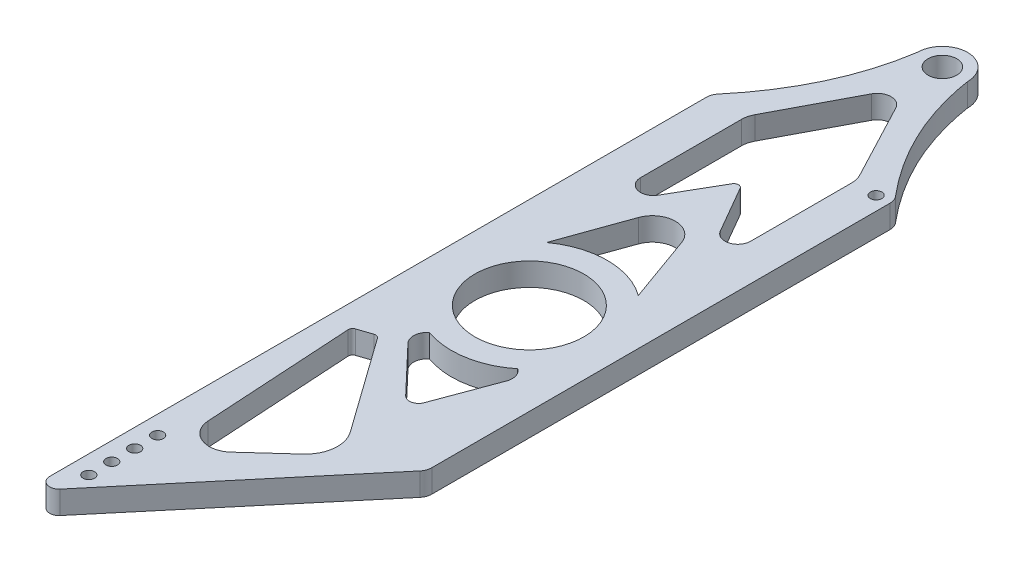
SolidWorks part; units mm, degrees
material "6061-T6 (SS)"
ref_plane "X-Y Datum" through (0, 0, 0) normal (0, 0, 1) x (1, 0, 0)
ref_plane "X-Z Datum" through (0, 0, 0) normal (0, 1, 0) x (1, 0, 0)
ref_plane "Y-Z Datum" through (0, 0, 0) normal (1, 0, 0) x (0, 0, -1)
other "Graphic1" [suppressed]
other "Graphic (Closed) -1" [suppressed]
sketch "Sketch1" plane through (0, 0, 0) normal (0, 1, 0) x (1, 0, 0)
  line L0 (25.4, -39.9268) -> (25.4, -166.6722)
  line L2 (-25.4, -221.6214) -> (-25.4, -39.9268)
  line L6 (25.4, -114.3) -> (-25.4, -114.3) construction
  line L9 (24.5086, -169.1212) -> (-20.9142, -223.2541)
  line L11 (5.6055, -169.4737) -> (-13.1669, -143.1763)
  line L13 (4.3503, -181.2166) -> (-6.1618, -190.7738)
  line L14 (-16.7719, -186.4583) -> (-19.261, -145.2583)
  line L15 (-18.3959, -143.9772) -> (-14.6031, -142.7097)
  line L16 (4.5321, -153.0605) -> (-7.7137, -140.1848)
  line L18 (14.9571, -135.5462) -> (8.7527, -152.1969)
  line L20 (-12.7, -96.8404) -> (-5.9766, -78.1113)
  line L21 (5.9766, -78.1113) -> (12.7, -96.8404)
  line L22 (-3.3709, -16.2433) -> (-14.5081, -37.3849)
  line L23 (-15.24, -40.3445) -> (-15.24, -68.2845)
  line L24 (-8.6044, -70.0625) -> (-1.0999, -57.0642)
  line L25 (1.0999, -57.0642) -> (8.6044, -70.0625)
  line L26 (15.24, -68.2845) -> (15.24, -40.3445)
  line L27 (14.5081, -37.3849) -> (3.3709, -16.2433)
  line L28 (8.89, -40.3445) -> (-8.89, -40.3445) construction
  line L29 (15.24, -55.1592) -> (-15.24, -55.1592) construction
  circle A0 centre (0, 0) radius 3.9688
  circle A2 centre (0, -114.3) radius 15.0813
  circle A6 centre (-20.32, -215.9) radius 1.5875
  circle A7 centre (-20.32, -209.55) radius 1.5875
  circle A8 centre (-20.32, -203.2) radius 1.5875
  circle A9 centre (-20.32, -196.85) radius 1.5875
  arc A10 (6.985, 0) -> (-6.985, 0) centre (0, 0) ccw
  arc A11 (-16.7719, -186.4583) -> (-6.1618, -190.7738) centre (-10.4335, -186.0754) ccw
  arc A12 (-18.3959, -143.9772) -> (-19.261, -145.2583) centre (-17.9933, -145.1817) ccw
  arc A13 (-14.6031, -142.7097) -> (-13.1669, -143.1763) centre (-14.2005, -143.9142) cw
  arc A14 (4.3503, -181.2166) -> (5.6055, -169.4737) centre (-1.6301, -174.6388) ccw
  arc A16 (13.5694, -131.0929) -> (14.9571, -135.5462) centre (11.3869, -134.2158) cw
  arc A17 (4.5321, -153.0605) -> (8.7527, -152.1969) centre (6.3726, -151.3101) ccw
  arc A21 (-3.3709, -16.2433) -> (3.3709, -16.2433) centre (0, -18.0191) cw
  arc A25 (14.5081, -37.3849) -> (15.24, -40.3445) centre (8.89, -40.3445) cw
  arc A26 (-14.5081, -37.3849) -> (-15.24, -40.3445) centre (-8.89, -40.3445) ccw
  arc A27 (13.5694, -131.0929) -> (-7.3523, -134.5995) centre (0, -114.3) cw
  arc A28 (-7.3523, -134.5995) -> (-7.7137, -140.1848) centre (-4.953, -137.5591) ccw
  arc A29 (-15.24, -68.2845) -> (-8.6044, -70.0625) centre (-11.684, -68.2845) ccw
  arc A30 (8.6044, -70.0625) -> (15.24, -68.2845) centre (11.684, -68.2845) ccw
  arc A31 (-1.0999, -57.0642) -> (1.0999, -57.0642) centre (0, -57.6992) cw
  arc A32 (12.7, -96.8404) -> (-12.7, -96.8404) centre (0, -114.3) ccw
  arc A33 (-5.9766, -78.1113) -> (5.9766, -78.1113) centre (0, -80.2568) cw
  arc A34 (24.5041, -37.4724) -> (25.4, -39.9268) centre (21.59, -39.9268) cw
  arc A35 (-24.5041, -37.4724) -> (-25.4, -39.9268) centre (-21.59, -39.9268) ccw
  arc A36 (25.4, -166.6722) -> (24.5086, -169.1212) centre (21.59, -166.6722) cw
  arc A37 (-25.4, -221.6214) -> (-20.9142, -223.2541) centre (-22.86, -221.6214) ccw
  circle A38 centre (21.59, -39.9268) radius 1.5875
  spline S0 degree 3 poles (24.5041, -37.4724) (15.363, -26.6191) (9.1782, -14.2) (6.985, 0) knots 0.031766 0.031766 0.031766 0.031766 1 1 1 1
  spline S1 degree 3 poles (-24.5041, -37.4724) (-15.3415, -26.5935) (-9.1434, -14.1045) (-6.985, 0) knots 0.031078 0.031078 0.031078 0.031078 1 1 1 1
  point P44 (0, -55.1592)
  point P58 (0, -40.3445)
  point P66 (25.4, -168.0589)
  point P68 (-15.24, -81.5557)
  point P71 (15.24, -81.5557)
  point P75 (15.24, -38.7742)
  point P78 (-15.24, -38.7742)
  point P80 (-25.4, -228.6)
  point P85 (-15.24, -81.5557)
  point P88 (15.24, -81.5557)
  point P92 (0, -55.1592)
  dimension "D1" = 7.9375
  dimension "D4" = 30.1625
  dimension "D8" = 3.175
  dimension "D6" = 6.985
  dimension "D18" = 6.35
  dimension "D19" = 1.27
  dimension "D20" = 1.27
  dimension "D21" = 8.89
  dimension "D28" = 3.81
  dimension "D29" = 2.54
  dimension "D32" = 3.81
  dimension "D33" = 6.35
  dimension "D37" = 21.59
  dimension "D41" = 3.81
  dimension "D46" = 3.556
  dimension "D47" = 1.27
  dimension "D49" = 21.59
  dimension "D31" = 6.35
  dimension "D17" = 3.81
  dimension "D52" = 3.81
  dimension "D55" = 3.81
  dimension "D56" = 2.54
  dimension "D43" = 22.352
  dimension "D44" = 22.352
  dimension "D53" = 3.175
  dimension "D2" = 228.6
  dimension "D3" = 114.3
  dimension "D9" = 5.08
  dimension "D10" = 12.7
  dimension "D11" = 6.35
  dimension "D12" = 6.35
  dimension "D13" = 6.35
  dimension "D5" = 50.8
  dimension "D7" = 140
  dimension "D14" = 19.05
  dimension "D16" = 12.7
  dimension "D22" = 18.0165
  dimension "D23" = 6.5799
  dimension "D24" = 107.042
  dimension "D25" = 105.022
  dimension "D26" = 3.999
  dimension "D34" = 32.3103
  dimension "D35" = 41.2751
  dimension "D36" = 27.8194
  dimension "D38" = 21.2136
  dimension "D39" = 16.7929
  dimension "D27" = 64
  dimension "D40" = 4.6645
  dimension "D42" = 5.597
  dimension "D45" = 60
  dimension "D48" = 27.94
  dimension "D30" = 25.4
  dimension "D50" = 30.48
  dimension "D51" = 19.8993
  dimension "D57" = 24.5041
  dimension "D58" = 37.4724
  dimension "D59" = 40.3445
  dimension "D60" = 18.0191
  dimension "D15" = 25.4
extrude "Boss-Extrude1" add sketch "Sketch1" against normal blind 6.35
sketch "Sketch4" plane through (0, 0, 0) normal (0, 1, 0) x (1, 0, 0)
  line L0 (0, -114.3) -> (0, 0)
  line L1 (0, 0) -> (101.9515, 0)
  line L2 (101.9515, 0) -> (0, -114.3)
  circle A0 centre (0, -114.3) radius 15.0813 construction
  point P2 (0, -115.7605)
  point P5 (0, 0)
  dimension "D1" = 48.268
  dimension "D2" = 153.162
sketch "Sketch8" plane through (-25.4, 0, 0) normal (-1, 0, 0) x (0, 0, 1)
  line L0 (190.5, 0) -> (190.5, -6.35)
  line L1 (39.9268, 0) -> (221.6214, 0) construction
  line L2 (39.9268, -6.35) -> (221.6214, -6.35) construction
  line L4 (228.6, -6.35) -> (228.6, 0) construction
  dimension "D1" = 38.1
split line "Split Line1"
equation "\"toePadMount\"=0.25"
equation "\"D11@Sketch1\"=\"toePadMount\""
equation "\"D12@Sketch1\"=\"toePadMount\""
equation "\"D13@Sketch1\"=\"toePadMount\""
